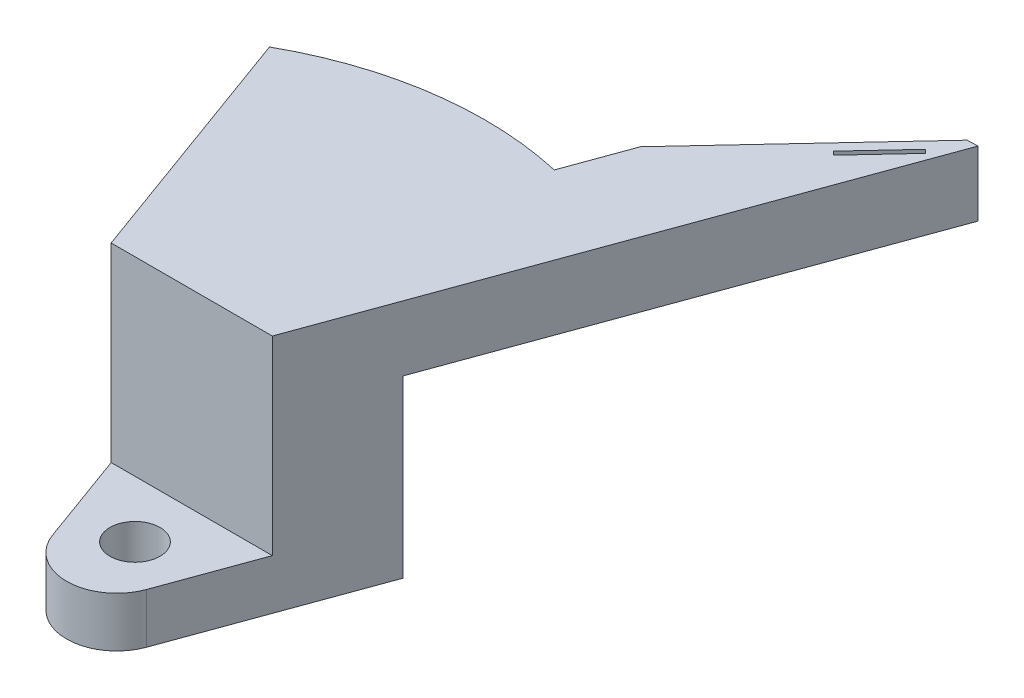
SolidWorks part; units mm, degrees
ref_plane "前视基准面" through (0, 0, 0) normal (0, 0, 1) x (1, 0, 0)
ref_plane "上视基准面" through (0, 0, 0) normal (0, 1, 0) x (1, 0, 0)
ref_plane "右视基准面" through (0, 0, 0) normal (1, 0, 0) x (0, 0, -1)
sketch "草图1" plane through (0, 0, 0) normal (0, 1, 0) x (1, 0, 0)
  line L0 (0, -1000) -> (0, 49000) construction
  line L1 (-34.202, 61.0755) -> (-9.3969, -7.0759)
  line L2 (34.202, 61.0755) -> (9.3969, -7.0759)
  circle A0 centre (0, 0) radius 70
  arc A1 (9.3969, -7.0759) -> (-9.3969, -7.0759) centre (0, -3.6557) cw
  circle A2 centre (0, 0) radius 5
  point P8 (0, -32.8937)
  dimension "D1" = 140
  dimension "D4" = 10
  dimension "D5" = 10
  dimension "D2" = 20
  dimension "D3" = 100
extrude "凸台-拉伸1" add sketch "草图1" along normal blind 48 contours A1 L0 A2 A0 L1 | L0 A1 L2 A0 A2
sketch "草图2" plane through (0, 48, 0) normal (0, 1, 0) x (1, 0, 0)
  line L0 (55.0345, 118.3122) -> (20.1256, 80.8771)
  line L1 (34.202, 61.0755) -> (9.3969, -7.0759) construction
  line L2 (36.2406, 125.1526) -> (55.0345, 118.3122)
  line L3 (36.2406, 125.1526) -> (5.4588, 40.5803)
  line L4 (5.4588, 40.5803) -> (24.2526, 33.7399)
  line L5 (55.0345, 118.3122) -> (24.2526, 33.7399)
  line L6 (36.2406, 125.1526) -> (24.2526, 33.7399) construction
  line L7 (5.4588, 40.5803) -> (55.0345, 118.3122) construction
  point P1 (30.2466, 79.4462)
  point P8 (-0.9024, -2.4793)
  dimension "D1" = 20
  dimension "D2" = 130
  dimension "D3" = 23
  dimension "D4" = 40
sketch "草图3" plane through (0, 0, 0) normal (0, 0, 1) x (1, 0, 0)
  line L0 (34.202, 48) -> (34.202, 0) construction
  line L1 (-34.202, 0) -> (-9.3969, 0) construction
  line L2 (-26.202, 8) -> (32.202, 8)
  line L3 (-26.202, 8) -> (-26.202, 2)
  line L4 (-26.202, 2) -> (32.202, 2)
  line L5 (32.202, 8) -> (32.202, 2)
  line L6 (-26.202, 8) -> (32.202, 2) construction
  line L7 (-26.202, 2) -> (32.202, 8) construction
  line L8 (-34.202, 48) -> (-34.202, 0) construction
  point P1 (3, 5)
  dimension "D1" = 2
  dimension "D2" = 8
  dimension "D3" = 6
  dimension "D4" = 2
extrude "切除-拉伸2" cut sketch "草图3" along normal blind 3 from surface starting at face at (0, 24, -65.5378)
extrude "凸台-拉伸2" add sketch "草图2" against normal blind 13
sketch "草图4" plane through (0, 0, 0) normal (1, 0, 0) x (0, 0, -1)
  line L0 (-13.6557, 48) -> (-13.6557, 0) construction
  line L1 (-13.6557, 48) -> (11.3443, 48)
  line L2 (-13.6557, 48) -> (-13.6557, 10)
  line L3 (-13.6557, 10) -> (11.3443, 10)
  line L4 (11.3443, 48) -> (11.3443, 10)
  line L5 (-13.6557, 48) -> (11.3443, 10) construction
  line L6 (-13.6557, 10) -> (11.3443, 48) construction
  line L8 (70.4669, 35) -> (30.4669, 35)
  line L9 (70.4669, 35) -> (70.4669, 10)
  line L10 (70.4669, 10) -> (30.4669, 10)
  line L11 (30.4669, 35) -> (30.4669, 10)
  line L12 (70.4669, 35) -> (30.4669, 10) construction
  line L13 (70.4669, 10) -> (30.4669, 35) construction
  line L14 (59.1533, 8) -> (67, 8) construction
  line L15 (-13.6557, 0) -> (-7.0759, 0) construction
  line L16 (118.3122, 35) -> (61.0755, 35) construction
  point P4 (-1.1557, 29)
  point P11 (50.4669, 22.5)
  dimension "D1" = 2
  dimension "D2" = 40
  dimension "D3" = 10
  dimension "D5" = 25
extrude "切除-拉伸3" cut sketch "草图4" against normal through all both and the other way through all
chamfer "倒角1" distance 5 angle 45 1 edges at (55.0345, 41.5, -118.3122)
sketch "草图6" plane through (0, 0, 0) normal (0, -1, 0) x (1, 0, 0)
  circle A0 centre (0, 0) radius 6.5
  dimension "D1" = 13
extrude "切除-拉伸4" cut sketch "草图6" against normal blind 2
sketch "草图7" plane through (0, 0, 0) normal (0, 0, 1) x (1, 0, 0)
  line L0 (-1024.202, 5) -> (48975.798, 5) construction
  line L1 (-26.202, 8) -> (-26.202, 2) construction
  line L2 (-34.202, 10) -> (-34.202, 0) construction
  circle A0 centre (-30.202, 5) radius 1.5
  point P5 (-26.202, 5)
  dimension "D1" = 3
  dimension "D2" = 4
extrude "切除-拉伸5" cut sketch "草图7" against normal blind 60
sketch "草图8" plane through (0, 10, 0) normal (0, 1, 0) x (1, 0, 0)
  line L0 (-34.202, 61.0755) -> (-16.1013, 11.3443) construction
  line L1 (-34.7582, 54.7401) -> (-25.7582, 54.7401)
  line L2 (-34.7582, 54.7401) -> (-34.7582, 45.7401)
  line L3 (-34.7582, 45.7401) -> (-25.7582, 45.7401)
  line L4 (-25.7582, 54.7401) -> (-25.7582, 45.7401)
  line L5 (-34.7582, 54.7401) -> (-25.7582, 45.7401) construction
  line L6 (-34.7582, 45.7401) -> (-25.7582, 54.7401) construction
  point P0 (-30.2582, 50.2401)
  dimension "D1" = 9
  dimension "D2" = 9
extrude "切除-拉伸6" cut sketch "草图8" against normal blind 11
sketch "草图10" plane through (10.5718, 0, 3.8478) normal (0.9397, 0, 0.342) x (0.342, 0, -0.9397)
  line L0 (-930.91, 5) -> (49069.09, 5) construction
  line L1 (69.09, 10) -> (69.09, 0) construction
  line L2 (67.59, -995) -> (67.59, 49005) construction
  circle A0 centre (67.59, 5) radius 1
  point P5 (69.09, 5)
  dimension "D1" = 2
  dimension "D2" = 1.5
extrude "切除-拉伸8" cut sketch "草图10" against normal up to surface (1.9464 mm away)
sketch "草图11" plane through (0, 0, -60) normal (0, 0, 1) x (1, 0, 0)
  circle A0 centre (-30.202, 5) radius 0.75
  dimension "D1" = 1.5
extrude "切除-拉伸9" cut sketch "草图11" against normal up to next
sketch "草图12" plane through (0, 10, 0) normal (0, 1, 0) x (1, 0, 0)
  line L1 (-1.653, 52.9115) -> (18.347, 52.9115)
  line L2 (-1.653, 52.9115) -> (-1.653, 49.9115)
  line L3 (-1.653, 49.9115) -> (18.347, 49.9115)
  line L4 (18.347, 52.9115) -> (18.347, 49.9115)
  line L5 (-1.653, 52.9115) -> (18.347, 49.9115) construction
  line L6 (-1.653, 49.9115) -> (18.347, 52.9115) construction
  point P0 (8.347, 51.4115)
  dimension "D1" = 3
  dimension "D2" = 20
  dimension "D3" = 15
extrude "切除-拉伸10" cut sketch "草图12" against normal blind 11
sketch "草图13" plane through (0, 10, 0) normal (0, 1, 0) x (1, 0, 0)
  line L0 (-976.6169, 51.4115) -> (49023.3831, 51.4115) construction
  line L1 (18.347, 49.9115) -> (18.347, 52.9115) construction
  line L3 (27.6086, 52.1615) -> (31.4769, 52.1615)
  line L4 (27.6086, 52.1615) -> (27.6086, 50.6615)
  line L5 (27.6086, 50.6615) -> (31.4769, 50.6615)
  line L6 (31.4769, 52.1615) -> (31.4769, 50.6615)
  line L7 (27.6086, 52.1615) -> (31.4769, 50.6615) construction
  line L8 (27.6086, 50.6615) -> (31.4769, 52.1615) construction
  point P4 (18.347, 51.4115)
  point P5 (29.5428, 51.4115)
  dimension "D1" = 1.5
extrude "切除-拉伸11" cut sketch "草图13" against normal blind 4
sketch "草图14" plane through (0, 48, 0) normal (0, 1, 0) x (1, 0, 0)
  line L0 (51.6245, 114.6554) -> (20.1256, 80.8771) construction
  line L1 (49.7661, 108.2233) -> (49.0348, 108.9053)
  line L2 (49.7661, 108.2233) -> (40.9002, 98.7157)
  line L3 (40.9002, 98.7157) -> (40.1688, 99.3977)
  line L4 (49.0348, 108.9053) -> (40.1688, 99.3977)
  line L5 (49.7661, 108.2233) -> (40.1688, 99.3977) construction
  line L6 (40.9002, 98.7157) -> (49.0348, 108.9053) construction
  line L9 (53.7303, 114.729) -> (16.1013, 11.3443) construction
  point P4 (44.9675, 103.8105)
  dimension "D1" = 1
  dimension "D2" = 13
  dimension "D3" = 13
  dimension "D4" = 1
  dimension "D5" = 90
  dimension "D6" = 4.5
  dimension "D7" = 14
extrude "切除-拉伸12" cut sketch "草图14" against normal up to next
sketch "草图15" plane through (0, 10, 0) normal (0, 1, 0) x (1, 0, 0)
  line L0 (-23.0614, 30.4669) -> (23.0614, 30.4669) construction
  line L1 (-48.3561, 85.9901) -> (46.5706, 85.9901)
  line L2 (-48.3561, 85.9901) -> (-48.3561, 30.4669)
  line L3 (-48.3561, 30.4669) -> (46.5706, 30.4669)
  line L4 (46.5706, 85.9901) -> (46.5706, 30.4669)
  line L5 (-48.3561, 85.9901) -> (46.5706, 30.4669) construction
  line L6 (-48.3561, 30.4669) -> (46.5706, 85.9901) construction
  point P4 (-0.8927, 58.2285)
  point P5 (-48.3561, 81.9699)
extrude "切除-拉伸13" cut sketch "草图15" against normal blind 10
